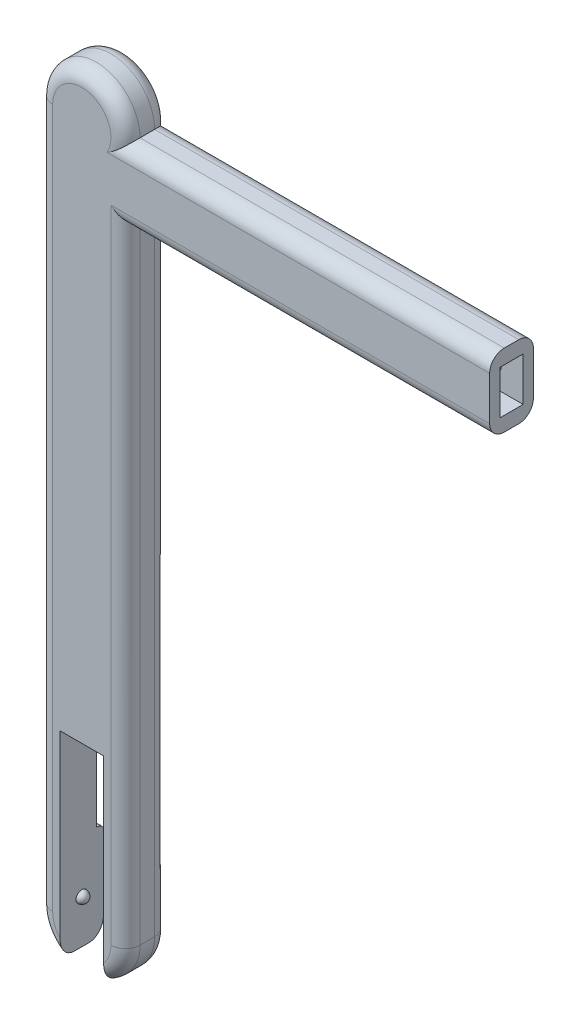
SolidWorks part; units mm, degrees
ref_plane "Front Plane" through (0, 0, 0) normal (0, 0, 1) x (1, 0, 0)
ref_plane "Top Plane" through (0, 0, 0) normal (0, 1, 0) x (1, 0, 0)
ref_plane "Right Plane" through (0, 0, 0) normal (1, 0, 0) x (0, 0, -1)
sketch "Sketch1" plane through (0, 0, 0) normal (0, 0, 1) x (1, 0, 0)
  line L0 (0, -103.2558) -> (0, 136.7442) construction
  line L1 (-15, -103.2558) -> (-15, 136.7442)
  line L2 (15, -103.2558) -> (15, 111.7442)
  line L3 (15, 136.7442) -> (140, 136.7442)
  line L4 (140, 136.7442) -> (140, 111.7442)
  line L5 (140, 111.7442) -> (15, 111.7442)
  arc A0 (-15, -103.2558) -> (15, -103.2558) centre (0, -103.2558) ccw
  arc A1 (15, 136.7442) -> (-15, 136.7442) centre (0, 136.7442) ccw
  point P3 (0, 16.7442)
  dimension "D2" = 15
  dimension "D1" = 240
  dimension "D3" = 125
  dimension "D4" = 25
extrude "Boss-Extrude1" add sketch "Sketch1" along normal blind 15
fillet "Fillet1" radius 5 12 edges at (0, 151.7442, 0) (-15, 16.7442, 0) (0, -118.2558, 0) (0, 151.7442, 15) (15, 4.2442, 15) (0, -118.2558, 15) (15, 4.2442, 0) (77.5, 136.7442, 15) (77.5, 136.7442, 0) (77.5, 111.7442, 0) (77.5, 111.7442, 15) (-15, 16.7442, 15)
sketch "Sketch2" plane through (140, 0, 0) normal (1, 0, 0) x (0, 0, -1)
  line L0 (-10, 111.7442) -> (-5, 111.7442) construction
  line L1 (-11.5, 131.7442) -> (-3.5, 131.7442)
  line L2 (-11.5, 131.7442) -> (-11.5, 116.7442)
  line L3 (-11.5, 116.7442) -> (-3.5, 116.7442)
  line L4 (-3.5, 131.7442) -> (-3.5, 116.7442)
  line L6 (-15, 116.7442) -> (-15, 131.7442) construction
  dimension "D1" = 8
  dimension "D2" = 15
  dimension "D3" = 5
  dimension "D4" = 3.5
extrude "Cut-Extrude1" cut sketch "Sketch2" against normal blind 100
sketch "Sketch3" plane through (0, 0, 15) normal (0, 0, 1) x (1, 0, 0)
  line L0 (-10, 136.7442) -> (-10, -103.2558) construction
  line L1 (-7.5, -118.2558) -> (7.5, -118.2558)
  line L2 (-7.5, -118.2558) -> (-7.5, -48.2558)
  line L3 (-7.5, -48.2558) -> (7.5, -48.2558)
  line L4 (7.5, -118.2558) -> (7.5, -48.2558)
  arc A0 (-15, -103.2558) -> (15, -103.2558) centre (0, -103.2558) ccw construction
  dimension "D1" = 15
  dimension "D2" = 70
  dimension "D3" = 2.5
extrude "Cut-Extrude3" cut sketch "Sketch3" against normal blind 100
ref_plane "Plane1" through (0, 0, 7.5) normal (0, 0, 1) x (1, 0, 0)
sketch "Sketch6" plane through (0, 0, 7.5) normal (0, 0, 1) x (1, 0, 0)
  line L0 (22.7951, -101.2558) -> (-27.1938, -101.2558) construction
  line L1 (7.5, -48.2558) -> (-7.5, -48.2558) construction
  line L2 (-7.5, -101.2558) -> (-5.5, -101.2558)
  line L3 (-7.5, -48.2558) -> (-7.5, -109.8702) construction
  line L4 (-7.5, -99.2558) -> (-7.5, -101.2558)
  line L5 (0, 28.4206) -> (0, -140.8487) construction
  line L6 (7.5, -101.2558) -> (5.5, -101.2558)
  line L7 (7.5, -109.8702) -> (7.5, -48.2558) construction
  line L8 (7.5, -99.2558) -> (7.5, -101.2558)
  arc A0 (-5.5, -101.2558) -> (-7.5, -99.2558) centre (-7.5, -101.2558) ccw
  arc A1 (5.5, -101.2558) -> (7.5, -99.2558) centre (7.5, -101.2558) cw
  dimension "D1" = 53
  dimension "D2" = 2
  dimension "D3" = 2
revolve "Revolve1" add sketch "Sketch6" angle 360 about L0
sketch "Sketch8" plane through (0, 0, 0) normal (1, 0, 0) x (0, 0, -1)
  line L1 (-7.5, 85.25) -> (-7.5, -85.25) construction
  line L2 (0, -103.2558) -> (0, 136.7442) construction
  line L6 (-7.5, 91.7442) -> (0, 86.4926)
  line L9 (-7.5, 81.7442) -> (-7.5, 91.7442)
  line L22 (-10, 136.7442) -> (-5, 136.7442) construction
  line L25 (0, 56.4926) -> (0, 66.4926)
  line L26 (-7.5, 71.7442) -> (0, 66.4926)
  line L27 (-7.5, 81.7442) -> (0, 76.4926)
  line L28 (0, 76.4926) -> (0, 86.4926)
  line L29 (-7.5, 61.7442) -> (-7.5, 71.7442)
  line L30 (-7.5, 61.7442) -> (0, 56.4926)
  line L31 (0, 36.4926) -> (0, 46.4926)
  line L32 (-7.5, 51.7442) -> (0, 46.4926)
  line L33 (-7.5, 41.7442) -> (-7.5, 51.7442)
  line L34 (-7.5, 41.7442) -> (0, 36.4926)
  dimension "D5" = 55
  dimension "D6" = 10
  dimension "D7" = 3
extrude "Cut-Extrude4" cut sketch "Sketch8" against normal mid plane 7.5
sketch "Sketch9" plane through (0, 0, 0) normal (0, 0, -1) x (-1, 0, 0)
  line L0 (-15, 111.7442) -> (-140, 111.7442) construction
  line L1 (-140, 116.7442) -> (-140, 131.7442) construction
  circle A0 centre (-130, 124.2442) radius 2.5
  circle A1 centre (-110, 124.2442) radius 2.5
  circle A2 centre (-90, 124.2442) radius 2.5
  circle A3 centre (-70, 124.2442) radius 2.5
  circle A4 centre (-50, 124.2442) radius 2.5
  dimension "D2" = 5
  dimension "D1" = 12.5
  dimension "D4" = 10
  dimension "D3" = 5
extrude "Cut-Extrude5" cut sketch "Sketch9" against normal blind 7.5
sketch "Sketch10" plane through (-15, 0, 0) normal (-1, 0, 0) x (0, 0, 1)
  line L0 (0, -83.2558) -> (2.5, -83.2558)
  line L1 (0, -103.2558) -> (0, 136.7442) construction
  line L2 (2.5, -83.2558) -> (2.5, 6.7442)
  line L3 (2.5, 6.7442) -> (0, 6.7442)
  line L4 (0, 6.7442) -> (0, -83.2558)
  dimension "D1" = 90
  dimension "D2" = 20
  dimension "D3" = 2.5
extrude "Cut-Extrude6" cut sketch "Sketch10" against normal through all
fillet "Fillet2" radius 2 7 edges at (12.5, 6.7442, 0.6699) (-12.5, 6.7442, 0.6699) (-12.5, -83.2558, 0.6699) (12.5, -83.2558, 0.6699) (0, 6.7442, 0) (-8.75, -83.2558, 0) (8.75, -83.2558, 0)
sketch "Sketch11" plane through (-15, 0, 0) normal (-1, 0, 0) x (0, 0, 1)
  line L0 (0, 109.2442) -> (0, 101.2442)
  line L1 (0, 8.7442) -> (0, 136.7442) construction
  line L4 (-3, 104.2442) -> (-7, 104.2442)
  line L5 (-7, 104.2442) -> (-7, 109.2442)
  line L6 (-7, 109.2442) -> (0, 109.2442)
  arc A0 (0, 101.2442) -> (-3, 104.2442) centre (-3, 101.2442) ccw
  dimension "D1" = 3
  dimension "D2" = 5
  dimension "D3" = 7
  dimension "D4" = 15.5
extrude "Boss-Extrude2" add sketch "Sketch11" against normal blind 19
sketch "Sketch12" plane through (0, 0, -7) normal (0, 0, -1) x (-1, 0, 0)
  line L0 (3.75, 100.7129) -> (3.75, 111.6456)
  line L1 (3.75, 111.6456) -> (16.7615, 111.6456)
  line L2 (16.7615, 111.6456) -> (16.7615, 100.7129)
  line L3 (16.7615, 100.7129) -> (3.75, 100.7129)
  line L4 (3.75, 91.7442) -> (3.75, 81.7442) construction
extrude "Cut-Extrude7" cut sketch "Sketch12" against normal blind 7
